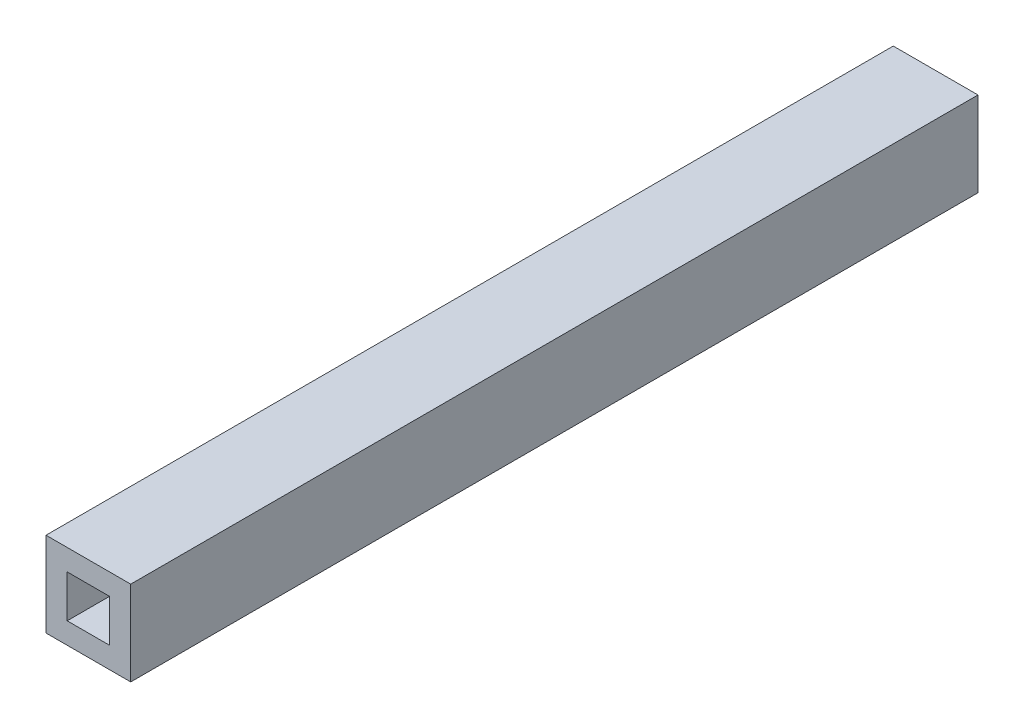
SolidWorks part; units mm, degrees
material "6063-O"
ref_plane "Front Plane" through (0, 0, 0) normal (0, 0, 1) x (1, 0, 0)
ref_plane "Top Plane" through (0, 0, 0) normal (0, 1, 0) x (1, 0, 0)
ref_plane "Right Plane" through (0, 0, 0) normal (1, 0, 0) x (0, 0, -1)
sketch "Sketch1" plane through (0, 0, 0) normal (0, 0, 1) x (1, 0, 0)
  line L1 (-10, -10) -> (10, -10)
  line L2 (-10, -10) -> (-10, 10)
  line L3 (-10, 10) -> (10, 10)
  line L4 (10, -10) -> (10, 10)
  line L5 (-10, -10) -> (10, 10) construction
  line L6 (-10, 10) -> (10, -10) construction
  point P0 (0, 0)
  dimension "D1" = 20
extrude "Extrude-Thin1" add sketch "Sketch1" along normal blind 200 thin thin type one direction reverse wall 5
